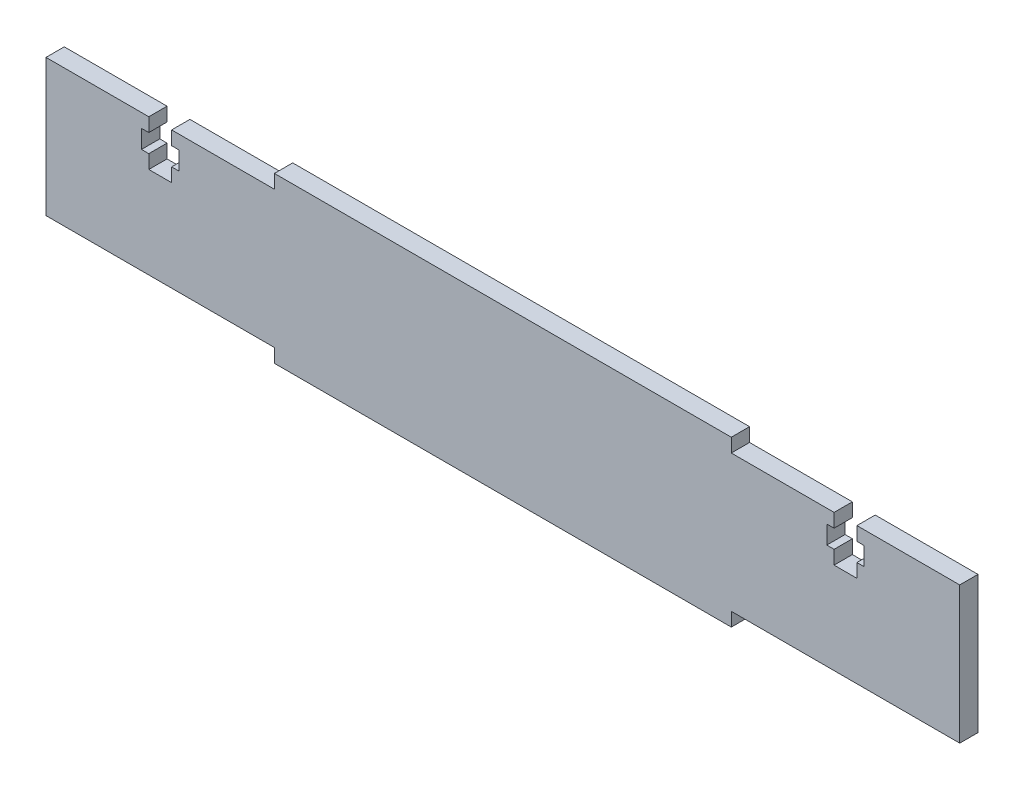
SolidWorks part; units mm, degrees
ref_plane "Front Plane" through (0, 0, 0) normal (0, 0, 1) x (1, 0, 0)
ref_plane "Top Plane" through (0, 0, 0) normal (0, 1, 0) x (1, 0, 0)
ref_plane "Right Plane" through (0, 0, 0) normal (1, 0, 0) x (0, 0, -1)
sketch "Sketch1" plane through (0, 0, 0) normal (0, 0, 1) x (1, 0, 0)
  line L1 (100, -15) -> (-100, -15)
  line L2 (100, -15) -> (100, 15)
  line L3 (100, 15) -> (-100, 15)
  line L4 (-100, -15) -> (-100, 15)
  line L5 (100, -15) -> (-100, 15) construction
  line L6 (100, 15) -> (-100, -15) construction
  line L7 (50, -18) -> (-50, -18)
  line L8 (50, -18) -> (50, -12)
  line L9 (50, -12) -> (-50, -12)
  line L10 (-50, -18) -> (-50, -12)
  line L11 (50, -18) -> (-50, -12) construction
  line L12 (50, -12) -> (-50, -18) construction
  line L13 (50, 12) -> (-50, 12)
  line L14 (50, 12) -> (50, 18)
  line L15 (50, 18) -> (-50, 18)
  line L16 (-50, 12) -> (-50, 18)
  line L17 (50, 12) -> (-50, 18) construction
  line L18 (50, 18) -> (-50, 12) construction
  point P0 (0, 0)
  point P6 (0, -15)
  point P11 (0, 15)
  dimension "D1" = 200
  dimension "D2" = 30
  dimension "D3" = 6
  dimension "D4" = 100
  dimension "D5" = 6
extrude "Boss-Extrude1" add sketch "Sketch1" along normal blind 4 contours L1 L10 L9 L8 L2 L3 L4 | L10 L7 L8 L1 | L10 L1 L8 L9 | L16 L3 L14 L15 | L16 L13 L14 L3
sketch "Sketch2" plane through (0, 0, 4) normal (0, 0, 1) x (1, 0, 0)
  line L0 (-50, 15) -> (-100, 15) construction
  line L1 (-77.5, 25) -> (-72.5, 25)
  line L2 (-77.5, 25) -> (-77.5, 5)
  line L3 (-77.5, 5) -> (-72.5, 5)
  line L4 (-72.5, 25) -> (-72.5, 5)
  line L5 (-77.5, 25) -> (-72.5, 5) construction
  line L6 (-77.5, 5) -> (-72.5, 25) construction
  line L8 (-70.9, 8) -> (-79.1, 8)
  line L9 (-70.9, 8) -> (-70.9, 12)
  line L10 (-70.9, 12) -> (-79.1, 12)
  line L11 (-79.1, 8) -> (-79.1, 12)
  line L12 (-70.9, 8) -> (-79.1, 12) construction
  line L13 (-70.9, 12) -> (-79.1, 8) construction
  point P0 (-75, 15)
  point P7 (-75, 10)
  dimension "D1" = 5
  dimension "D2" = 20
  dimension "D3" = 8.2
  dimension "D4" = 0
  dimension "D5" = 4
  dimension "D6" = 3
extrude "Cut-Extrude1" cut sketch "Sketch2" against normal blind 10 contours L4 L3 L2 L1 | L10 L11 L8 L9
mirror "Mirror1" about plane through (0, 0, 0) normal (1, 0, 0) of "Cut-Extrude1"
